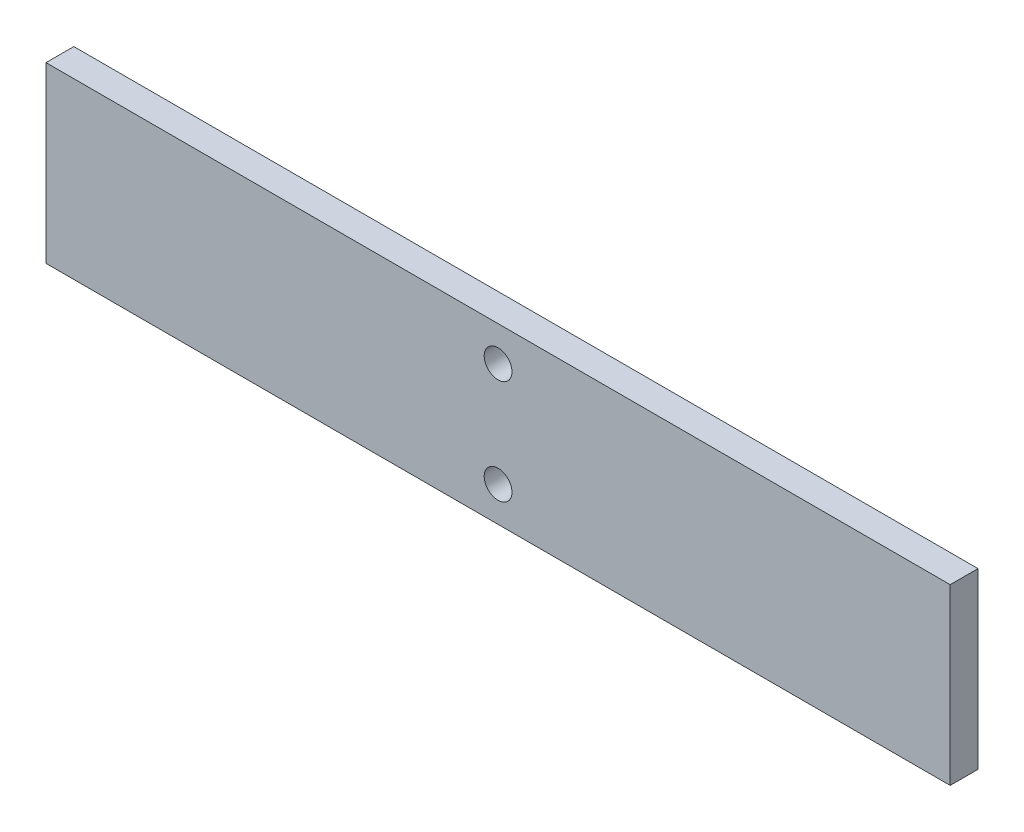
SolidWorks part; units mm, degrees
ref_plane "Front Plane" through (0, 0, 0) normal (0, 0, 1) x (1, 0, 0)
ref_plane "Top Plane" through (0, 0, 0) normal (0, 1, 0) x (1, 0, 0)
ref_plane "Right Plane" through (0, 0, 0) normal (1, 0, 0) x (0, 0, -1)
sketch "草图1" plane through (0, 0, 0) normal (0, 0, 1) x (1, 0, 0)
  line L1 (0, 10) -> (52, 10)
  line L2 (0, 10) -> (0, 0)
  line L3 (0, 0) -> (52, 0)
  line L4 (52, 10) -> (52, 0)
extrude "凸台-拉伸1" add sketch "草图1" along normal blind 1.6
sketch "草图2" plane through (0, 0, 0) normal (0, 0, 1) x (1, 0, 0)
  circle A0 centre (26, 2) radius 0.8
  circle A1 centre (26, 8) radius 0.8
extrude "切除-拉伸1" cut sketch "草图2" along normal blind 1.6
sketch "草图3" plane through (0, 0, 1.6) normal (0, 0, 1) x (1, 0, 0)
  circle A0 centre (8, 5) radius 2
  circle A1 centre (44, 5) radius 2
